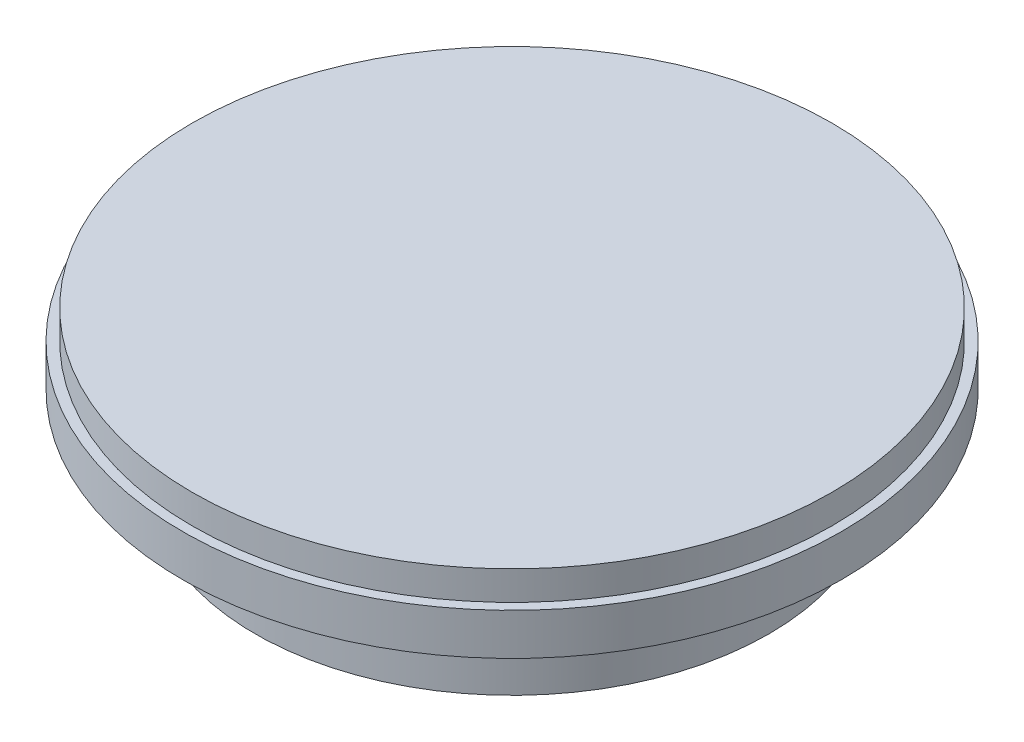
SolidWorks part; units mm, degrees
ref_plane "Front" through (0, 0, 0) normal (0, 0, 1) x (1, 0, 0)
ref_plane "Top" through (0, 0, 0) normal (0, 1, 0) x (1, 0, 0)
ref_plane "Right" through (0, 0, 0) normal (1, 0, 0) x (0, 0, -1)
sketch "Sketch2" plane through (0, 0, 0) normal (0, 0, 1) x (1, 0, 0)
  line L0 (0, -6.45) -> (0, 6.45)
  line L1 (0, -6.45) -> (26.5, -6.45)
  line L2 (26.5, -6.45) -> (26.5, -0.85)
  line L3 (26.5, -0.85) -> (34, 2.15)
  line L4 (34, 2.15) -> (34, 6.45)
  line L5 (0, 6.45) -> (34, 6.45)
  point P4 (0, 0)
  dimension "D1" = 26.5
  dimension "D2" = 5.6
  dimension "D3" = 34
  dimension "D4" = 3
  dimension "D5" = 4.3
revolve "Revolve1" add sketch "Sketch2" angle 360 about L0
sketch "Sketch3" plane through (0, 6.45, 0) normal (0, 1, 0) x (1, 0, 0)
  circle A0 centre (0, 0) radius 33
  circle A1 centre (0, 0) radius 34 construction
  dimension "D1" = 1
extrude "Boss-Extrude1" add sketch "Sketch3" along normal blind 3
sketch "Sketch4" plane through (0, -6.45, 0) normal (0, -1, 0) x (1, 0, 0)
  line L0 (0, 0) -> (0, 15) construction
  line L1 (10.6066, -10.6066) -> (-10.6066, 10.6066) construction
  line L2 (-10.6066, -10.6066) -> (10.6066, 10.6066) construction
  circle A0 centre (0, 0) radius 15 construction
  point P7 (0, 0)
  point P9 (0, 0)
  dimension "D2" = 30
  dimension "D1" = 45
hole_wizard "M3x0.5 Tapped Hole1" positions "Sketch5" profile "Sketch6" tap size "M3x0.5" standard "ANSI Metric"
sketch "Sketch5" plane through (0, -6.45, 0) normal (0, -1, 0) x (-1, 0, 0)
  point P0 (10.6066, -10.6066)
  point P3 (-10.6066, -10.6066)
  point P6 (-10.6066, 10.6066)
  point P9 (10.6066, 10.6066)
sketch "Sketch6" plane through (-10.6066, -6.45, 10.6066) normal (1, 0, 0) x (0, 0, -1)
  line L0 (0, 0) -> (0, 8.2511)
  line L1 (0, 8.2511) -> (1.25, 7.5)
  line L2 (1.25, 7.5) -> (1.25, 0)
  line L5 (1.25, 0) -> (0, 0)
  line L10 (0, 8.2511) -> (-1.25, 7.5) construction
  line L11 (0, -6.35) -> (0, 107.95) construction
  dimension "Tap Drill Dia." = 2.5
  dimension "Tap Drill Depth" = 7.5
  dimension "Drill Angle" = 118
cosmetic thread "Hole Thread1" parameters "D1"=6, "D2"=3
cosmetic thread "Hole Thread2" parameters "D1"=6, "D2"=3
cosmetic thread "Hole Thread3" parameters "D1"=6, "D2"=3
cosmetic thread "Hole Thread4" parameters "D1"=6, "D2"=3
